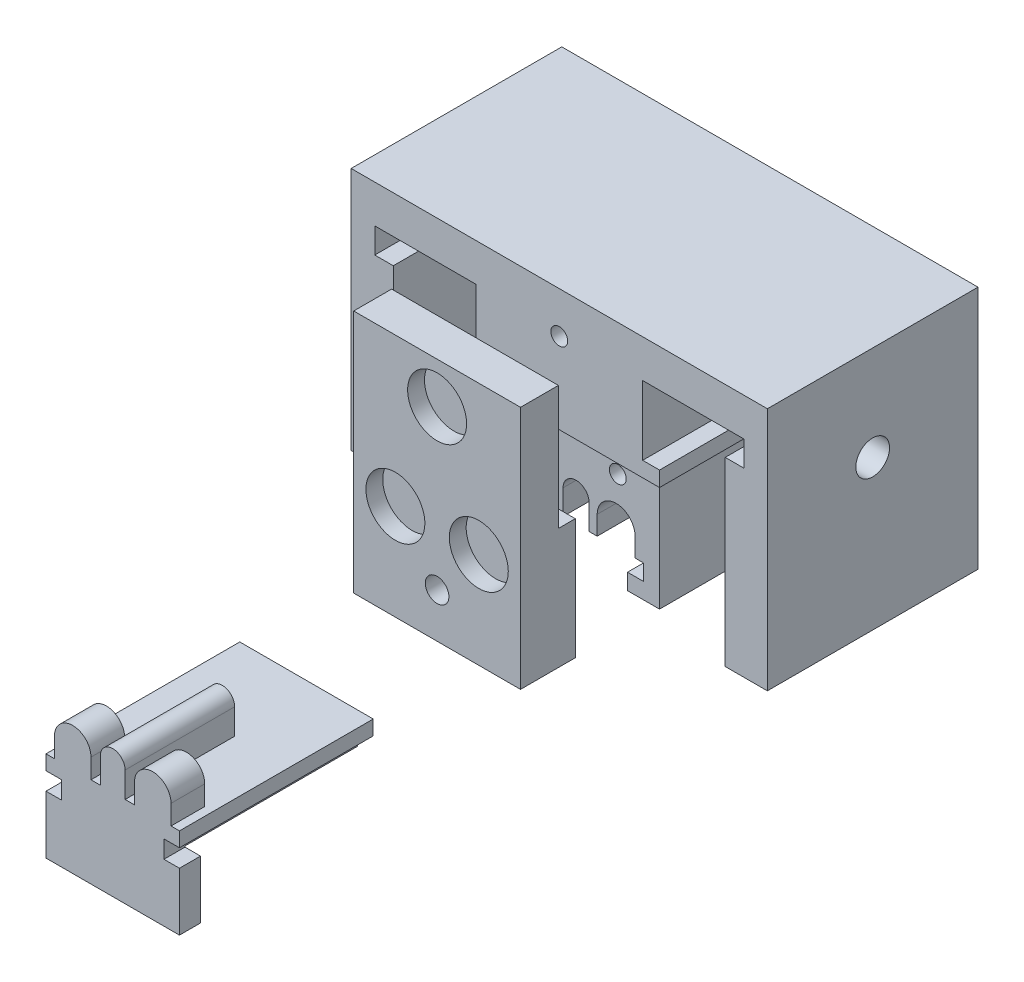
SolidWorks part; units mm, degrees
ref_plane "Front Plane" through (0, 0, 0) normal (0, 0, 1) x (1, 0, 0)
ref_plane "Top Plane" through (0, 0, 0) normal (0, 1, 0) x (1, 0, 0)
ref_plane "Right Plane" through (0, 0, 0) normal (1, 0, 0) x (0, 0, -1)
sketch "Sketch1" plane through (0, 0, 0) normal (0, 0, 1) x (1, 0, 0)
  line L0 (-21.9, 7) -> (-21.9, 10)
  line L1 (-21.9, 10) -> (-9.9, 10)
  line L2 (-9.9, 10) -> (-9.9, 1.8)
  line L3 (-9.9, -14.5) -> (9.9, -14.5)
  line L4 (9.9, -14.5) -> (9.9, 0)
  line L5 (9.9, 10) -> (21.9, 10)
  line L6 (21.9, 10) -> (21.9, 7)
  line L7 (19.7, -14.5) -> (24.7, -14.5)
  line L8 (24.7, -14.5) -> (24.7, 14.5)
  line L9 (24.7, 14.5) -> (-24.7, 14.5)
  line L14 (-24.7, 14.5) -> (-24.7, -14.5)
  line L16 (-21.9, 7) -> (-19.7, 7)
  line L17 (-19.7, 7) -> (-19.7, -14.5)
  line L18 (-19.7, -14.5) -> (-24.7, -14.5)
  line L19 (21.9, 7) -> (19.7, 7)
  line L20 (19.7, 7) -> (19.7, -14.5)
  line L22 (-9.9, 1.8) -> (-11.9, 1.8)
  line L23 (-11.9, 1.8) -> (-11.9, 0)
  line L24 (-11.9, 0) -> (-9.9, 0)
  line L25 (9.9, 1.8) -> (11.9, 1.8)
  line L26 (11.9, 1.8) -> (11.9, 0)
  line L27 (11.9, 0) -> (9.9, 0)
  line L28 (-9.9, 0) -> (-9.9, -14.5)
  line L29 (9.9, 1.8) -> (9.9, 10)
  point P9 (-24.7, 0)
  point P29 (0, -14.5)
  dimension "D1" = 19.8
  dimension "D2" = 12
  dimension "D3" = 4.5
  dimension "D4" = 4.5
  dimension "D5" = 24.5
  dimension "D6" = 5
  dimension "D7" = 2.2
  dimension "D8" = 1.8
  dimension "D9" = 14.5
  dimension "D10" = 3
  dimension "D11" = 2
extrude "Boss-Extrude1" add sketch "Sketch1" along normal blind 25
sketch "Sketch2" plane through (-24.7, 0, 0) normal (-1, 0, 0) x (0, 0, 1)
  line L0 (25, 1.8) -> (0, 1.8) construction
  line L2 (25, 1.8) -> (0, 1.8) construction
  line L3 (9.1108, 1.25) -> (17.7065, 1.25) construction
  circle A0 centre (12.5, 3.25) radius 2
  point P3 (12.5, 1.8)
  dimension "D1" = 4
  dimension "D2" = 0.55
extrude "Cut-Extrude1" cut sketch "Sketch2" against normal through all
sketch "Sketch5" plane through (0, 0, 0) normal (1, 0, 0) x (0, 0, -1)
  line L1 (-8.4008, 3.25) -> (-10.4504, 6.8)
  line L2 (-10.4504, 6.8) -> (-14.5496, 6.8)
  line L3 (-14.5496, 6.8) -> (-16.5992, 3.25)
  line L4 (-16.5992, 3.25) -> (-14.5496, -0.3)
  line L5 (-14.5496, -0.3) -> (-10.4504, -0.3)
  line L6 (-10.4504, -0.3) -> (-8.4008, 3.25)
  circle A2 centre (-12.5, 3.25) radius 3.55 construction
  dimension "D1" = 7.1
extrude "Cut-Extrude2" cut sketch "Sketch5" against normal blind 6 and the other way blind 6
sketch "Sketch6" plane through (0, 0, 0) normal (0, 0, 1) x (1, 0, 0)
  line L0 (6, 6.8) -> (-6, 6.8) construction
  line L1 (3, 6.8) -> (-3, 6.8)
  line L2 (3, 6.8) -> (3, -0.3)
  line L3 (3, -0.3) -> (-3, -0.3)
  line L4 (-3, 6.8) -> (-3, -0.3)
  line L5 (6, -0.3) -> (-6, -0.3) construction
  point P9 (0, -0.3)
  dimension "D1" = 6
extrude "Cut-Extrude3" cut sketch "Sketch6" along normal up to vertex
sketch "Sketch9" plane through (0, 0, 25) normal (0, 0, 1) x (1, 0, 0)
  line L2 (-6.1, -14.5) -> (6.1, -14.5)
  line L4 (-9.9, -14.5) -> (9.9, -14.5) construction
  line L5 (6.1, -14.5) -> (6.1, -12.6)
  line L6 (6.1, -12.6) -> (8, -12.6)
  line L7 (8, -12.6) -> (8, -10.7)
  line L8 (8, -10.7) -> (-8, -10.7)
  line L9 (-8, -10.7) -> (-8, -12.6)
  line L10 (-8, -12.6) -> (-6.1, -12.6)
  line L11 (-6.1, -12.6) -> (-6.1, -14.5)
  line L12 (-9.9, 0) -> (-9.9, -14.5) construction
  line L14 (-9.9, -12.6) -> (-8, -12.6) construction
  point P12 (0, -10.7)
  dimension "D1" = 1.9
extrude "Cut-Extrude4" cut sketch "Sketch9" against normal up to next
sketch "Sketch11" plane through (0, 0, 25) normal (0, 0, 1) x (1, 0, 0)
  line L0 (-8, -10.7) -> (-8, -12.6) construction
  line L2 (8, -12.6) -> (8, -10.7) construction
  line L3 (-7, -8.45) -> (-7, -10.7)
  line L4 (-2.5, -8.45) -> (-2.5, -10.7)
  line L5 (2.5, -8.45) -> (2.5, -10.7)
  line L6 (7, -8.45) -> (7, -10.7)
  line L7 (-7, -10.7) -> (-2.5, -10.7)
  line L8 (2.5, -10.7) -> (7, -10.7)
  line L9 (-4.75, -8.45) -> (-4.75, -6.2) construction
  line L10 (8, -10.7) -> (-8, -10.7) construction
  line L12 (-1.55, -7.75) -> (-1.55, -10.7)
  line L13 (-1.55, -10.7) -> (1.55, -10.7)
  line L14 (1.55, -7.75) -> (1.55, -10.7)
  arc A0 (-2.5, -8.45) -> (-7, -8.45) centre (-4.75, -8.45) ccw
  arc A1 (7, -8.45) -> (2.5, -8.45) centre (4.75, -8.45) ccw
  arc A2 (-1.55, -7.75) -> (1.55, -7.75) centre (0, -7.75) cw
  point P22 (0, -6.2)
  point P23 (4.75, -6.2)
  dimension "D1" = 4.5
  dimension "D2" = 1
  dimension "D3" = 1
  dimension "D4" = 3.1
extrude "Cut-Extrude5" cut sketch "Sketch11" against normal blind 23
sketch "Sketch12" plane through (0, 0, 25) normal (0, 0, 1) x (1, 0, 0)
  line L0 (6.1, -14.5) -> (9.9, -14.5) construction
  line L1 (-9.9, 0) -> (9.9, 0)
  line L2 (-9.9, 0) -> (-9.9, -14.5)
  line L3 (-9.9, -14.5) -> (9.9, -14.5)
  line L4 (9.9, 0) -> (9.9, -14.5)
  line L5 (-9.9, 0) -> (9.9, -14.5) construction
  line L6 (-9.9, -14.5) -> (9.9, 0) construction
  line L7 (-9.9, 0) -> (-9.9, -14.5) construction
  line L8 (9.9, -14.5) -> (9.9, 0) construction
  line L9 (9.9, 0) -> (11.9, 0) construction
  point P0 (0, -7.25)
extrude "Cut-Extrude6" cut sketch "Sketch12" against normal blind 2
sketch "Sketch13" plane through (0, 0, 23) normal (0, 0, 1) x (1, 0, 0)
  line L0 (0, 0) -> (0, -6.2) construction
  line L1 (9.9, 0) -> (-9.9, 0) construction
  line L2 (-9.9, -3.1) -> (0, -3.1) construction
  line L5 (-9.9, 0) -> (-9.9, -14.5) construction
  line L6 (0, -3.1) -> (9.9, -3.1) construction
  line L7 (9.9, -14.5) -> (9.9, 0) construction
  line L9 (6, 6.8) -> (-6, 6.8) construction
  line L10 (6, 6.8) -> (-6, 6.8) construction
  line L11 (6, -0.3) -> (-6, -0.3) construction
  line L12 (6, -0.3) -> (-6, -0.3) construction
  line L13 (-4.95, -3.1) -> (-4.95, -0.3) construction
  line L14 (0, 9.6) -> (0, 6.8) construction
  circle A0 centre (-4.95, -3.1) radius 1
  circle A1 centre (4.95, -3.1) radius 1
  arc A2 (1.55, -7.75) -> (-1.55, -7.75) centre (0, -7.75) ccw construction
  circle A3 centre (0, 9.6) radius 1
  point P15 (0, -3.1)
  point P20 (-4.95, -3.1)
  point P21 (4.95, -3.1)
  dimension "D1" = 2
extrude "Cut-Extrude7" cut sketch "Sketch13" against normal blind 12 and the other way blind 2
ref_plane "Plane1" through (0, 0, 35) normal (0, 0, 1) x (1, 0, 0)
sketch "Sketch14" plane through (0, 0, 35) normal (0, 0, 1) x (1, 0, 0)
  line L8 (-9.9, 14.5) -> (-9.9, -14.5)
  line L9 (-9.9, -14.5) -> (9.9, -14.5)
  line L10 (9.9, -14.5) -> (9.9, 14.5)
  line L11 (24.7, 14.5) -> (-24.7, 14.5) construction
  line L12 (9.9, 14.5) -> (-9.9, 14.5)
  circle A6 centre (0, 9.6) radius 1.25
  circle A7 centre (-4.95, -3.1) radius 1.25
  circle A8 centre (4.95, -3.1) radius 1.25
  dimension "D1" = 2.5
extrude "Boss-Extrude2" add sketch "Sketch14" along normal blind 4.5 separate body
sketch "Sketch15" plane through (0, 0, 35) normal (0, 0, -1) x (-1, 0, 0)
  line L0 (9.9, -0.2) -> (-9.9, -0.2)
  line L1 (9.9, 14.5) -> (9.9, -14.5) construction
  line L2 (11.9, 0) -> (-11.9, 0) construction
  line L4 (-9.9, -14.5) -> (-9.9, 14.5) construction
  line L5 (-9.9, -0.2) -> (-9.9, -14.5)
  line L6 (-9.9, -14.5) -> (9.9, -14.5)
  line L7 (9.9, -14.5) -> (9.9, -0.2)
  circle A0 centre (4.95, -3.1) radius 1.25 construction
  circle A1 centre (-4.95, -3.1) radius 1.25 construction
  circle A2 centre (4.95, -3.1) radius 1.25
  circle A3 centre (-4.95, -3.1) radius 1.25
  dimension "D1" = 0.2
extrude "Boss-Extrude3" add sketch "Sketch15" along normal blind 2
sketch "Sketch16" plane through (0, 0, 39.5) normal (0, 0, 1) x (1, 0, 0)
  circle A0 centre (4.95, -3.1) radius 3.5
  circle A1 centre (-4.95, -3.1) radius 3.5
  circle A2 centre (0, 9.6) radius 3.5
  dimension "D1" = 7
extrude "Cut-Extrude8" cut sketch "Sketch16" against normal blind 2
sketch "Sketch17" plane through (0, 0, 37.5) normal (0, 0, 1) x (1, 0, 0)
  circle A0 centre (0, 9.6) radius 1.25 construction
  circle A1 centre (-4.95, -3.1) radius 1.25 construction
  circle A2 centre (4.95, -3.1) radius 1.25 construction
  circle A3 centre (0, 9.6) radius 1.25
  circle A4 centre (-4.95, -3.1) radius 1.25
  circle A5 centre (4.95, -3.1) radius 1.25
extrude "Boss-Extrude4" add sketch "Sketch17" against normal blind 0.6
sketch "Sketch18" plane through (0, 0, 33) normal (0, 0, -1) x (-1, 0, 0)
  line L1 (-3.1754, -9.225) -> (-1.5877, -11.975)
  line L2 (-1.5877, -11.975) -> (1.5877, -11.975)
  line L3 (1.5877, -11.975) -> (3.1754, -9.225)
  line L4 (3.1754, -9.225) -> (1.5877, -6.475)
  line L5 (1.5877, -6.475) -> (-1.5877, -6.475)
  line L6 (-1.5877, -6.475) -> (-3.1754, -9.225)
  line L7 (1.55, -10.7) -> (1.55, -7.75) construction
  circle A1 centre (0, -9.225) radius 2.75 construction
  point P14 (1.55, -9.225)
  dimension "D1" = 5.5
extrude "Cut-Extrude9" cut sketch "Sketch18" against normal blind 2.6
sketch "Sketch19" plane through (0, 0, 35.6) normal (0, 0, -1) x (-1, 0, 0)
  line L0 (1.5877, -6.475) -> (-1.5877, -6.475) construction
  circle A0 centre (0, -9.225) radius 1.4
  point P5 (0, -6.475)
  dimension "D1" = 2.8
extrude "Cut-Extrude10" cut sketch "Sketch19" against normal up to next (3.9 mm away)
ref_plane "Plane2" through (0, 0, 55) normal (0, 0, 1) x (1, 0, 0)
sketch "Sketch20" plane through (0, 0, 55) normal (0, 0, 1) x (1, 0, 0)
  line L0 (-1.55, -10.7) -> (-1.55, -7.75) construction
  line L1 (7, -8.45) -> (7, -10.7) construction
  line L2 (-2.5, -8.45) -> (-2.5, -10.7) construction
  line L3 (-6.08, -12.52) -> (-7.92, -12.52)
  line L4 (-7.92, -12.52) -> (-7.92, -10.78)
  line L5 (-6.1, -12.6) -> (-8, -12.6) construction
  line L6 (-8, -12.6) -> (-8, -10.7) construction
  line L7 (-8, -10.7) -> (-7, -10.7) construction
  line L8 (1.55, -10.7) -> (2.5, -10.7) construction
  line L9 (-2.5, -10.7) -> (-1.55, -10.7) construction
  line L10 (-7, -10.7) -> (-7, -8.45) construction
  line L11 (-7.92, -10.78) -> (-6.92, -10.78)
  line L12 (-6.92, -10.78) -> (-6.92, -8.45)
  line L13 (8, -12.6) -> (6.1, -12.6) construction
  line L14 (8, -10.7) -> (8, -12.6) construction
  line L15 (7, -10.7) -> (8, -10.7) construction
  line L16 (2.5, -10.7) -> (2.5, -8.45) construction
  line L17 (1.55, -7.75) -> (1.55, -10.7) construction
  line L18 (-2.58, -8.45) -> (-2.58, -10.78)
  line L19 (-2.58, -10.78) -> (-1.47, -10.78)
  line L20 (-6.1, -12.6) -> (-8, -12.6) construction
  line L21 (-8, -12.6) -> (-8, -10.7) construction
  line L22 (-8, -10.7) -> (-7, -10.7) construction
  line L23 (1.55, -10.7) -> (2.5, -10.7) construction
  line L24 (-2.5, -10.7) -> (-1.55, -10.7) construction
  line L25 (-7, -10.7) -> (-7, -8.45) construction
  line L26 (-1.47, -10.78) -> (-1.47, -7.75)
  line L27 (1.47, -7.75) -> (1.47, -10.78)
  line L28 (8, -12.6) -> (6.1, -12.6) construction
  line L29 (8, -10.7) -> (8, -12.6) construction
  line L30 (7, -10.7) -> (8, -10.7) construction
  line L31 (2.5, -10.7) -> (2.5, -8.45) construction
  line L32 (1.55, -7.75) -> (1.55, -10.7) construction
  line L33 (-1.55, -10.7) -> (-1.55, -7.75) construction
  line L34 (-2.5, -8.45) -> (-2.5, -10.7) construction
  line L35 (7, -8.45) -> (7, -10.7) construction
  line L36 (1.47, -10.78) -> (2.58, -10.78)
  line L37 (2.58, -10.78) -> (2.58, -8.45)
  line L38 (6.92, -8.45) -> (6.92, -10.78)
  line L39 (6.92, -10.78) -> (7.92, -10.78)
  line L40 (7.92, -10.78) -> (7.92, -12.52)
  line L41 (7.92, -12.52) -> (6.08, -12.52)
  line L42 (-6.08, -12.52) -> (-6.08, -14.5)
  line L43 (-6.08, -14.5) -> (6.08, -14.5)
  line L44 (6.08, -14.5) -> (6.08, -12.52)
  line L45 (7.92, -12.52) -> (6.1, -12.52) construction
  line L46 (-6.1, -12.52) -> (-7.92, -12.52) construction
  line L47 (-9.9, -14.5) -> (-6.1, -14.5) construction
  line L48 (-6.1, -14.5) -> (-6.1, -12.6) construction
  line L49 (6.1, -12.6) -> (6.1, -14.5) construction
  arc A0 (7, -8.45) -> (2.5, -8.45) centre (4.75, -8.45) ccw construction
  arc A1 (1.55, -7.75) -> (-1.55, -7.75) centre (0, -7.75) ccw construction
  arc A2 (-2.5, -8.45) -> (-7, -8.45) centre (-4.75, -8.45) ccw construction
  arc A3 (-2.5, -8.45) -> (-7, -8.45) centre (-4.75, -8.45) ccw construction
  arc A4 (1.55, -7.75) -> (-1.55, -7.75) centre (0, -7.75) ccw construction
  arc A5 (7, -8.45) -> (2.5, -8.45) centre (4.75, -8.45) ccw construction
  arc A6 (-2.58, -8.45) -> (-6.92, -8.45) centre (-4.75, -8.45) ccw
  arc A7 (1.47, -7.75) -> (-1.47, -7.75) centre (0, -7.75) ccw
  arc A8 (6.92, -8.45) -> (2.58, -8.45) centre (4.75, -8.45) ccw
  dimension "D1" = 0.08
  dimension "D2" = 0.02
  dimension "D3" = 0.02
extrude "Boss-Extrude5" add sketch "Sketch20" along normal blind 23 separate body
sketch "Sketch21" plane through (0, -14.5, 0) normal (0, -1, 0) x (1, 0, 0)
  line L0 (-6.08, 78) -> (6.08, 78)
  line L1 (6.08, 78) -> (6.08, 75.5)
  line L2 (6.08, 78) -> (6.08, 55) construction
  line L3 (6.08, 75.5) -> (-6.08, 75.5)
  line L4 (-6.08, 78) -> (-6.08, 55) construction
  line L5 (-6.08, 75.5) -> (-6.08, 78)
  dimension "D1" = 2.5
extrude "Boss-Extrude6" add sketch "Sketch21" along normal blind 7
sketch "Sketch22" plane through (0, 0, 55) normal (0, 0, -1) x (-1, 0, 0)
  line L17 (7.92, -12.52) -> (7.92, -10.78)
  line L18 (7.92, -10.78) -> (6.92, -10.78)
  line L19 (6.92, -10.78) -> (6.92, -8.45)
  line L20 (2.58, -8.45) -> (2.58, -10.78)
  line L21 (2.58, -10.78) -> (1.47, -10.78)
  line L22 (1.47, -10.78) -> (1.47, -7.75)
  line L23 (-1.47, -7.75) -> (-1.47, -10.78)
  line L24 (-1.47, -10.78) -> (-2.58, -10.78)
  line L25 (-2.58, -10.78) -> (-2.58, -8.45)
  line L26 (-6.92, -8.45) -> (-6.92, -10.78)
  line L27 (-6.92, -10.78) -> (-7.92, -10.78)
  line L28 (-7.92, -10.78) -> (-7.92, -12.52)
  line L29 (-7.92, -12.52) -> (-6.08, -12.52)
  line L30 (-6.08, -12.52) -> (-6.08, -14.5)
  line L31 (-6.08, -14.5) -> (6.08, -14.5)
  line L32 (6.08, -14.5) -> (6.08, -12.52)
  line L33 (6.08, -12.52) -> (7.92, -12.52)
  line L36 (6.92, -10.78) -> (6.92, -8.45)
  line L37 (2.58, -8.45) -> (2.58, -10.78)
  line L38 (6.92, -10.78) -> (-1.47, -10.78)
  line L39 (1.47, -10.78) -> (1.47, -7.75)
  line L40 (-1.47, -7.75) -> (-1.47, -10.78)
  line L41 (-1.47, -10.78) -> (-6.92, -10.78)
  line L42 (-2.58, -10.78) -> (-2.58, -8.45)
  line L43 (-6.92, -8.45) -> (-6.92, -10.78)
  arc A3 (6.92, -8.45) -> (2.58, -8.45) centre (4.75, -8.45) ccw
  arc A4 (1.47, -7.75) -> (-1.47, -7.75) centre (0, -7.75) ccw
  arc A5 (-2.58, -8.45) -> (-6.92, -8.45) centre (-4.75, -8.45) ccw
  arc A6 (6.92, -8.45) -> (2.58, -8.45) centre (4.75, -8.45) ccw
  arc A7 (1.47, -7.75) -> (-1.47, -7.75) centre (0, -7.75) ccw
  arc A8 (-2.58, -8.45) -> (-6.92, -8.45) centre (-4.75, -8.45) ccw
  line M23 (6.92, -10.78) -> (6.92, -8.45)
  arc M24 (6.92, -8.45) -> (2.58, -8.45) centre (4.75, -8.45) ccw
  line M25 (2.58, -8.45) -> (2.58, -10.78)
  line M27 (1.47, -10.78) -> (1.47, -7.75)
  arc M28 (1.47, -7.75) -> (-1.47, -7.75) centre (0, -7.75) ccw
  line M29 (-1.47, -7.75) -> (-1.47, -10.78)
  line M31 (-2.58, -10.78) -> (-2.58, -8.45)
  arc M32 (-2.58, -8.45) -> (-6.92, -8.45) centre (-4.75, -8.45) ccw
  line M33 (-6.92, -8.45) -> (-6.92, -10.78)
  dimension "D1" = 0
extrude "Cut-Extrude11" cut sketch "Sketch22" against normal offset from surface (10 mm away) 13 contours L38 M23 M24 M25 | L38 M27 M28 M29 | L41 M31 M32 M33 up to face at (0, -11.1405, 78)
sketch "Sketch23" plane through (0, 0, 65) normal (0, 0, -1) x (-1, 0, 0)
  line L0 (6.92, -10.78) -> (6.92, -8.45) construction
  line L1 (2.58, -8.45) -> (2.58, -10.78) construction
  line L2 (2.58, -10.78) -> (6.92, -10.78) construction
  line L3 (-2.58, -10.78) -> (-2.58, -8.45) construction
  line L4 (-6.92, -8.45) -> (-6.92, -10.78) construction
  line L5 (-6.92, -10.78) -> (-2.58, -10.78) construction
  line L6 (6.92, -10.78) -> (6.92, -8.45)
  line L7 (2.58, -8.45) -> (2.58, -10.78)
  line L8 (2.58, -10.78) -> (6.92, -10.78)
  line L9 (-2.58, -10.78) -> (-2.58, -8.45)
  line L10 (-6.92, -8.45) -> (-6.92, -10.78)
  line L11 (-6.92, -10.78) -> (-2.58, -10.78)
  arc A0 (6.92, -8.45) -> (2.58, -8.45) centre (4.75, -8.45) ccw construction
  arc A1 (-2.58, -8.45) -> (-6.92, -8.45) centre (-4.75, -8.45) ccw construction
  arc A2 (6.92, -8.45) -> (2.58, -8.45) centre (4.75, -8.45) ccw
  arc A3 (-2.58, -8.45) -> (-6.92, -8.45) centre (-4.75, -8.45) ccw
extrude "Cut-Extrude12" cut sketch "Sketch23" against normal blind 9
sketch "Sketch25" plane through (0, 0, 78) normal (0, 0, 1) x (1, 0, 0)
  line L5 (-6.08, -12.52) -> (-6.08, -21.5) construction
  line L6 (-6.08, -14.62) -> (-7.92, -14.62)
  line L7 (-6.08, -14.62) -> (-6.08, -21.5)
  line L8 (-6.08, -21.5) -> (-7.92, -21.5)
  line L9 (-7.92, -14.62) -> (-7.92, -21.5)
  line L10 (6.08, -21.5) -> (6.08, -12.52) construction
  line L11 (6.08, -14.62) -> (7.92, -14.62)
  line L12 (6.08, -14.62) -> (6.08, -21.5)
  line L13 (6.08, -21.5) -> (7.92, -21.5)
  line L14 (7.92, -14.62) -> (7.92, -21.5)
  line L15 (7.92, -12.52) -> (7.92, -10.78) construction
  line L16 (-7.92, -10.78) -> (-7.92, -12.52) construction
  line L17 (-6.08, -14.5) -> (6.08, -14.5) construction
  point P21 (-6.08, -14.1033)
  dimension "D1" = 0.12
extrude "Boss-Extrude7" add sketch "Sketch25" against normal up to surface (2.5 mm away) up to face at (0, -18, 75.5)
